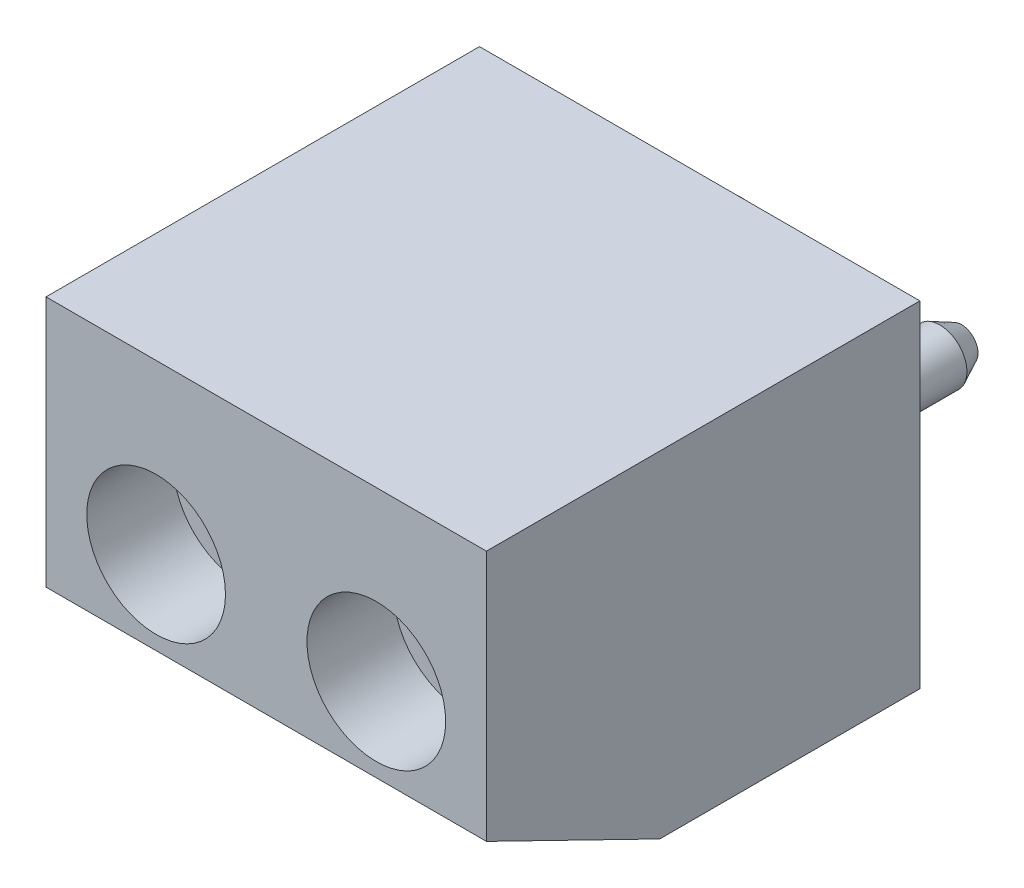
SolidWorks part; units mm, degrees
ref_plane "Front Plane" through (0, 0, 0) normal (0, 0, 1) x (1, 0, 0)
ref_plane "Top Plane" through (0, 0, 0) normal (0, 1, 0) x (1, 0, 0)
ref_plane "Right Plane" through (0, 0, 0) normal (1, 0, 0) x (0, 0, -1)
sketch "Sketch1" plane through (0, 0, 0) normal (0, 0, 1) x (1, 0, 0)
  line L1 (-5.08, -3.875) -> (5.08, -3.875)
  line L2 (-5.08, -3.875) -> (-5.08, 3.875)
  line L3 (-5.08, 3.875) -> (5.08, 3.875)
  line L4 (5.08, -3.875) -> (5.08, 3.875)
  point P4 (5.08, 0)
  point P6 (0, -3.875)
  dimension "D1" = 10.16
  dimension "D2" = 7.75
extrude "Boss-Extrude1" add sketch "Sketch1" along normal blind 10
chamfer "Chamfer1" distance 4 angle 26 1 edges at (0, -3.875, 10)
sketch "Sketch2" plane through (0, 0, 10) normal (0, 0, 1) x (1, 0, 0)
  line L0 (0, 1.9449) -> (0, -1.5927) construction
  circle A0 centre (-2.54, 0) radius 1.6
  circle A1 centre (2.54, 0) radius 1.6
  point P7 (0, 0)
  dimension "D2" = 3.2
  dimension "D1" = 5.08
extrude "Cut-Extrude1" cut sketch "Sketch2" against normal blind 2
sketch "Sketch3" plane through (0, -3.875, 0) normal (0, -1, 0) x (1, 0, 0)
  line L0 (0, 0) -> (0, 6) construction
  line L1 (-4.83, 5.75) -> (-0.25, 5.75)
  line L2 (-4.83, 5.75) -> (-4.83, 0.25)
  line L3 (-4.83, 0.25) -> (-0.25, 0.25)
  line L4 (-0.25, 5.75) -> (-0.25, 0.25)
  line L5 (0.25, 5.75) -> (4.83, 5.75)
  line L6 (0.25, 5.75) -> (0.25, 0.25)
  line L7 (0.25, 0.25) -> (4.83, 0.25)
  line L8 (4.83, 5.75) -> (4.83, 0.25)
  line L9 (5.08, 6) -> (-5.08, 6) construction
  line L10 (-5.08, 6) -> (-5.08, 0) construction
  line L11 (5.08, 6) -> (5.08, 0) construction
  line L12 (-5.08, 0) -> (5.08, 0) construction
  dimension "D1" = 0.25
  dimension "D2" = 0.5
  dimension "D3" = 0.25
  dimension "D4" = 0.25
  dimension "D5" = 0.25
extrude "Cut-Extrude2" cut sketch "Sketch3" against normal blind 1
sketch "Sketch4" plane through (0, -2.875, 0) normal (0, -1, 0) x (1, 0, 0)
  line L0 (0, 0) -> (0, 6) construction
  line L1 (5.08, 6) -> (-5.08, 6) construction
  line L2 (-4.83, 0.25) -> (-0.25, 0.25) construction
  line L3 (-4.83, 0.25) -> (-0.25, 0.25) construction
  circle A0 centre (-2.54, 2.5) radius 1.9
  circle A1 centre (2.54, 2.5) radius 1.9
  point P9 (0, 0)
  point P12 (0, 0)
  point P15 (-2.54, 0.25)
  dimension "D1" = 3.8
  dimension "D2" = 2.25
extrude "Cut-Extrude3" cut sketch "Sketch4" against normal blind 5
sketch "Sketch5" plane through (0, 0, 0) normal (0, 0, -1) x (-1, 0, 0)
  line L0 (0, -0.5909) -> (0, 0.8962) construction
  circle A0 centre (2.54, 0) radius 0.625
  circle A1 centre (-2.54, 0) radius 0.625
  point P7 (0, 0)
  dimension "D2" = 1.25
  dimension "D1" = 5.08
extrude "Boss-Extrude2" add sketch "Sketch5" along normal blind 3.5
chamfer "Chamfer2" distance 0.5 angle 26 2 edges at (1.915, 0, -3.5) (-3.165, 0, -3.5)
